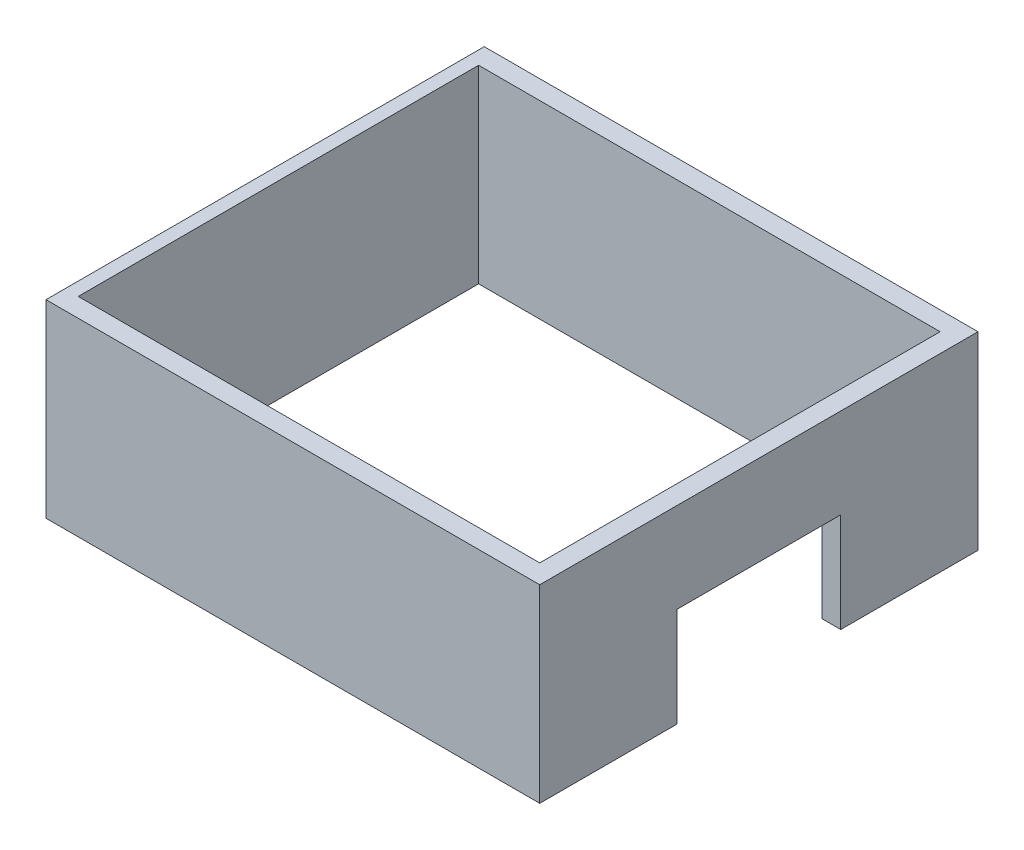
SolidWorks part; units mm, degrees
material "PE Alta densidad"
ref_plane "Alzado" through (0, 0, 0) normal (0, 0, 1) x (1, 0, 0)
ref_plane "Planta" through (0, 0, 0) normal (0, 1, 0) x (1, 0, 0)
ref_plane "Vista lateral" through (0, 0, 0) normal (1, 0, 0) x (0, 0, -1)
sketch "Croquis1" plane through (0, 0, 0) normal (0, 1, 0) x (1, 0, 0)
  line L0 (-27.499, -21.15) -> (21.2592, -21.15)
  line L1 (0, -21.15) -> (-27.499, -21.15) construction
  line L2 (-27.499, -21.15) -> (-27.499, 21.15) construction
  line L3 (0, -21.15) -> (21.2592, -21.15)
  line L4 (21.2592, -21.15) -> (21.2592, 21.15)
  line L5 (21.2592, 21.15) -> (-27.499, 21.15)
  line L10 (21.2592, -23.15) -> (-28.9031, -23.15) construction
  line L11 (-28.9031, -23.15) -> (-28.9031, 23.15) construction
  line L12 (-28.9031, 23.15) -> (23.2592, 23.15) construction
  line L13 (23.2592, 23.15) -> (23.2592, -23.15) construction
  line L14 (23.2592, -23.15) -> (21.2592, -23.15) construction
  line L15 (-28.9031, 23.15) -> (-28.9031, -23.15)
  line L16 (-28.9031, -23.15) -> (23.2592, -23.15)
  line L17 (23.2592, -23.15) -> (23.2592, 23.15)
  line L18 (23.2592, 23.15) -> (-28.9031, 23.15)
  line L19 (-27.499, 21.15) -> (-27.499, -21.15)
  line L20 (-27.499, -21.15) -> (21.2592, -21.15)
  line L21 (21.2592, 21.15) -> (-27.499, 21.15)
  line L22 (21.2592, 21.15) -> (21.2592, -21.15)
extrude "Saliente-Extruir1" add sketch "Croquis1" along normal blind 20 contours L17 L18 L15 L16 L19 L5 L4 L0
sketch "Croquis2" plane through (23.2592, 0, 0) normal (1, 0, 0) x (0, 0, -1)
  line L0 (-23.15, 0) -> (-8.65, 0) construction
  line L1 (-23.15, 0) -> (23.15, 0) construction
  line L2 (23.15, 0) -> (8.65, 0) construction
  line L3 (-8.65, 0) -> (-8.65, 10.5)
  line L4 (-8.65, 10.5) -> (8.65, 10.5)
  line L5 (8.65, 10.5) -> (8.65, 0)
  line L6 (8.65, 0) -> (-8.65, 0)
  dimension "D1" = 14.5
  dimension "D2" = 14.5
  dimension "D3" = 10.5
extrude "Cortar-Extruir1" cut sketch "Croquis2" against normal blind 20
